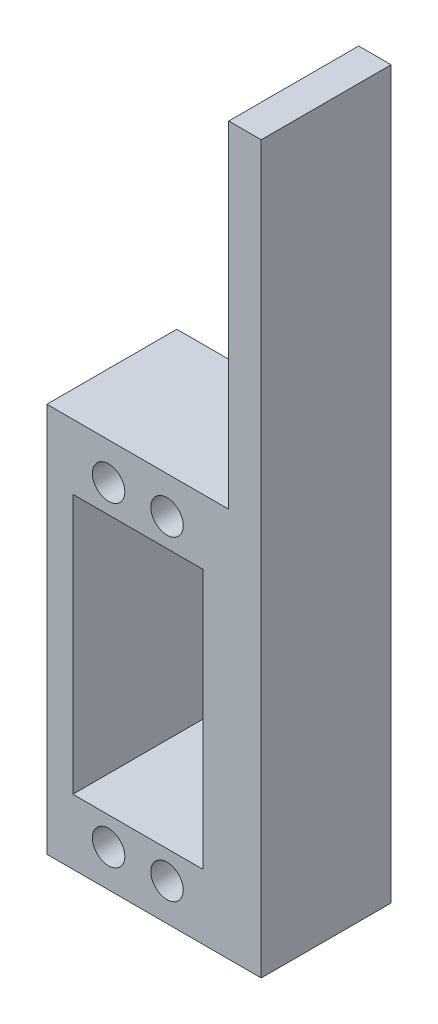
SolidWorks part; units mm, degrees
ref_plane "Plano frontal" through (0, 0, 0) normal (0, 0, 1) x (1, 0, 0)
ref_plane "Plano superior" through (0, 0, 0) normal (0, 1, 0) x (1, 0, 0)
ref_plane "Plano direito" through (0, 0, 0) normal (1, 0, 0) x (0, 0, -1)
sketch "Esboço1" plane through (0, 0, 0) normal (0, 0, 1) x (1, 0, 0)
  line L3 (2.324, -5.6986) -> (-17.676, -5.6986)
  line L4 (-17.676, 34.3014) -> (-17.676, -5.6986)
  line L6 (-17.676, 34.3014) -> (2.324, 34.3014)
  line L7 (2.324, 34.3014) -> (2.324, -5.6986)
  line L8 (2.324, -15.6986) -> (-17.676, -15.6986)
  line L10 (-21.676, 34.3014) -> (-21.676, -15.6986)
  line L11 (-21.676, -15.6986) -> (-17.676, -15.6986)
  line L12 (2.324, -15.6986) -> (6.324, -15.6986)
  line L13 (6.324, -15.6986) -> (6.324, 34.3014)
  line L15 (-21.676, 34.3014) -> (-21.676, 44.3014)
  line L16 (-21.676, 44.3014) -> (6.324, 44.3014)
  line L17 (6.324, 44.3014) -> (6.324, 34.3014)
  circle A0 centre (-12.176, -9.9986) radius 2.5
  circle A1 centre (-3.176, -9.9986) radius 2.5
  circle A2 centre (-12.176, 38.6014) radius 2.5
  circle A3 centre (-3.176, 38.6014) radius 2.5
  point P20 (-7.676, 44.3014)
  point P21 (-7.676, -5.6986)
  dimension "D7" = 5
  dimension "D8" = 5
  dimension "D9" = 5
  dimension "D10" = 4.3
  dimension "3" = 5
  dimension "D14" = 9
  dimension "D15" = 9
  dimension "D1" = 40
  dimension "D2" = 20
  dimension "D3" = 10
  dimension "D4" = 4
  dimension "D5" = 4
  dimension "D6" = 10
  dimension "D11" = 4.3
  dimension "D12" = 4.3
  dimension "D13" = 4.3
  dimension "D16" = 4.5
  dimension "D17" = 4.5
extrude "Ressalto-extrusão1" add sketch "Esboço1" along normal blind 20
sketch "Esboço2" plane through (0, 0, 0) normal (0, 0, -1) x (-1, 0, 0)
  line L0 (-6.324, 44.3014) -> (-6.324, -15.6986)
  line L4 (21.676, -15.6986) -> (-6.324, -15.6986) construction
  line L5 (-6.324, -15.6986) -> (-11.324, -15.6986)
  line L6 (-11.324, -15.6986) -> (-11.324, 96.0698)
  line L7 (-6.324, 44.3014) -> (-6.324, 96.0698)
  line L8 (-6.324, 96.0698) -> (-11.324, 96.0698)
  point P9 (7.676, -15.6986)
  dimension "D2" = 19
extrude "Ressalto-extrusão2" add sketch "Esboço2" against normal blind 20
